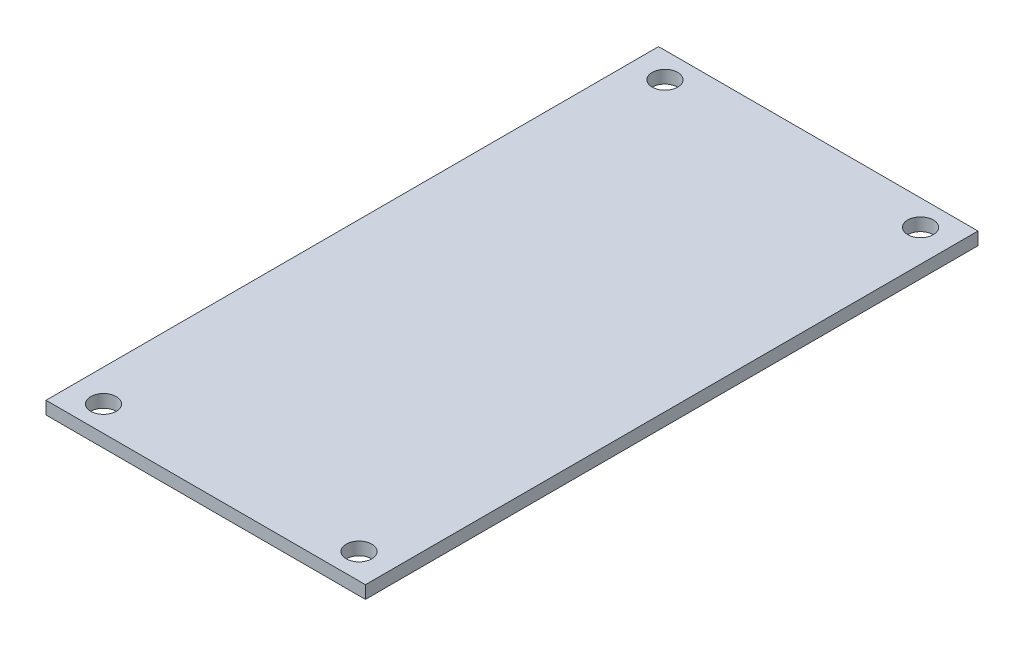
SolidWorks part; units mm, degrees
ref_plane "Front Plane" through (0, 0, 0) normal (0, 0, 1) x (1, 0, 0)
ref_plane "Top Plane" through (0, 0, 0) normal (0, 1, 0) x (1, 0, 0)
ref_plane "Right Plane" through (0, 0, 0) normal (1, 0, 0) x (0, 0, -1)
sketch "Sketch1" plane through (0, 0, 0) normal (0, 1, 0) x (1, 0, 0)
  line L1 (0, 0) -> (125, 0)
  line L2 (0, 0) -> (0, -239.7125)
  line L3 (0, -239.7125) -> (125, -239.7125)
  line L4 (125, 0) -> (125, -239.7125)
  dimension "D1" = 125
  dimension "D2" = 239.7125
extrude "Boss-Extrude1" add sketch "Sketch1" along normal blind 5
sketch "Sketch2" plane through (0, 0, 0) normal (0, -1, 0) x (1, 0, 0)
  line L0 (0, 0) -> (0, 239.7125) construction
  line L1 (0, 239.7125) -> (125, 239.7125) construction
  line L3 (125, 0) -> (0, 0) construction
  line L4 (125, 239.7125) -> (125, 0) construction
  circle A0 centre (12.5, 229.7125) radius 5
  circle A1 centre (112.5, 229.7125) radius 5
  circle A2 centre (12.5, 10) radius 5
  circle A3 centre (112.5, 10) radius 5
  point P0 (12.5, 229.7125)
  point P1 (112.5, 229.7125)
  point P6 (12.5, 10)
  point P7 (112.5, 10)
  dimension "D9" = 10
  dimension "D1" = 100
  dimension "D2" = 12.5
  dimension "D3" = 10
  dimension "D4" = 10
  dimension "D5" = 10
  dimension "D6" = 12.5
  dimension "D7" = 10
  dimension "D8" = 12.5
extrude "Cut-Extrude1" cut sketch "Sketch2" against normal up to next
sketch "Sketch3" plane through (0, 0, 0) normal (0, -1, 0) x (1, 0, 0)
  line L0 (0, 119.8563) -> (125, 119.8563) construction
  line L2 (125, 239.7125) -> (125, 0) construction
  line L3 (0, 0) -> (0, 239.7125) construction
  line L4 (62.5, 239.7125) -> (62.5, 0) construction
  line L6 (125, 0) -> (0, 0) construction
  line L7 (0, 239.7125) -> (125, 239.7125) construction
  point P0 (62.5, 119.8563)
  point P5 (62.5, 119.8563)
  point P12 (62.5, 119.8563)
  point P17 (20.7776, 318.2217)
